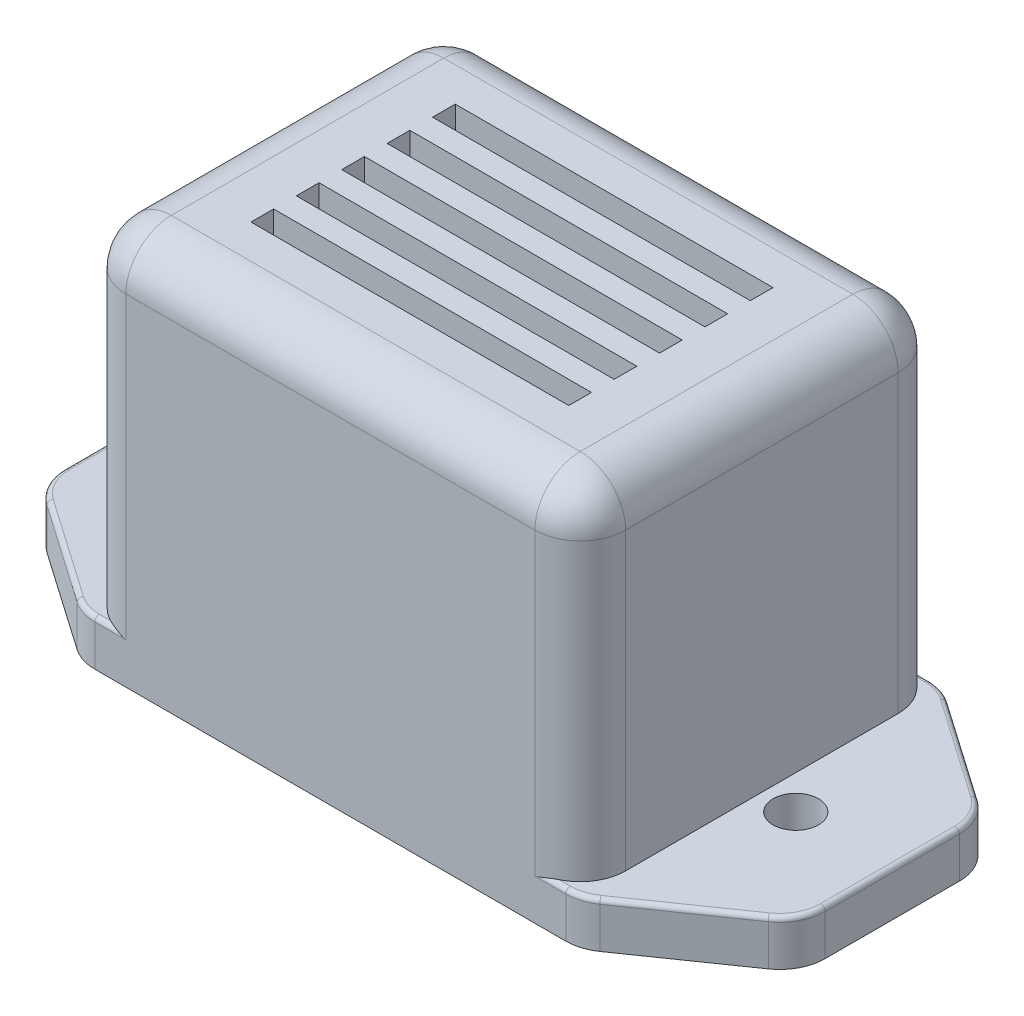
SolidWorks part; units mm, degrees
ref_plane "前视基准面" through (0, 0, 0) normal (0, 0, 1) x (1, 0, 0)
ref_plane "上视基准面" through (0, 0, 0) normal (0, 1, 0) x (1, 0, 0)
ref_plane "右视基准面" through (0, 0, 0) normal (1, 0, 0) x (0, 0, -1)
sketch "草图1" plane through (0, 0, 0) normal (0, 1, 0) x (1, 0, 0)
  line L0 (0, 0) -> (-16.75, 0) construction
  line L1 (-16.75, -4) -> (-16.75, 4)
  line L3 (10.3728, 8) -> (-10.3728, 8)
  line L4 (10.3728, -8) -> (-10.3728, -8)
  line L6 (11, 8) -> (-11, -8) construction
  line L7 (11, -8) -> (-11, 8) construction
  line L8 (0, 0) -> (0, 8) construction
  line L9 (-16.75, 4) -> (-11.5149, 7.6418)
  line L10 (-16.75, -4) -> (-11.5149, -7.6418)
  line L11 (16.75, -4) -> (11.5149, -7.6418)
  line L12 (16.75, -4) -> (16.75, 4)
  line L13 (16.75, 4) -> (11.5149, 7.6418)
  arc A0 (-10.3728, 8) -> (-11.5149, 7.6418) centre (-10.3728, 6) ccw
  arc A1 (10.3728, 8) -> (11.5149, 7.6418) centre (10.3728, 6) cw
  arc A2 (10.3728, -8) -> (11.5149, -7.6418) centre (10.3728, -6) ccw
  arc A3 (-10.3728, -8) -> (-11.5149, -7.6418) centre (-10.3728, -6) cw
  dimension "D5" = 4
  dimension "D1" = 16.75
  dimension "D2" = 4
  dimension "D3" = 22
  dimension "D4" = 16
extrude "凸台-拉伸1" add sketch "草图1" along normal blind 2
sketch "草图2" plane through (0, 2, 0) normal (0, 1, 0) x (1, 0, 0)
  line L0 (11.0073, 8) -> (11.0073, -8)
  line L1 (11.0073, 8) -> (-11.0073, 8)
  line L2 (11.0073, -8) -> (-11.0073, -8)
  line L3 (-11.0073, 8) -> (-11.0073, -8)
  line L4 (11.0073, 8) -> (-11.0073, -8) construction
  line L5 (11.0073, -8) -> (-11.0073, 8) construction
  point P1 (0, 0)
extrude "凸台-拉伸2" add sketch "草图2" along normal blind 15
sketch "草图3" plane through (0, 0, 0) normal (0, -1, 0) x (1, 0, 0)
  line L0 (0, 0) -> (-12.5, 0) construction
  circle A0 centre (-12.5, 0) radius 1
  dimension "D2" = 2
  dimension "D1" = 12.5
extrude "切除-拉伸1" cut sketch "草图3" against normal up to next
mirror "镜向1" about plane through (0, 0, 0) normal (1, 0, 0) of "切除-拉伸1"
sketch "草图4" plane through (0, 17, 0) normal (0, 1, 0) x (1, 0, 0)
  line L0 (0, 0) -> (-7, 0) construction
  line L1 (0, 0) -> (7, 0) construction
  line L2 (0, 0.5) -> (7, 0.5)
  line L3 (0, 0.5) -> (-7, 0.5)
  line L4 (0, -0.5) -> (7, -0.5)
  line L5 (0, -0.5) -> (-7, -0.5)
  line L6 (-7, 0.5) -> (-7, -0.5)
  line L7 (7, 0.5) -> (7, -0.5)
  dimension "D1" = 7
  dimension "D2" = 7
  dimension "D3" = 0.5
  dimension "D4" = 0.5
extrude "切除-拉伸2" cut sketch "草图4" against normal blind 1
pattern_linear "阵列(线性)1" count 3 spacing 2 along (0, 0, 1) count 3 spacing 2 along (0, 0, -1) of "切除-拉伸2"
sketch "草图5" plane through (0, 16, 0) normal (0, 1, 0) x (1, 0, 0)
  line L0 (9, 6) -> (9, -6)
  line L1 (9, 6) -> (-9, 6)
  line L2 (9, -6) -> (-9, -6)
  line L3 (-9, 6) -> (-9, -6)
  line L4 (9, 6) -> (-9, -6) construction
  line L5 (9, -6) -> (-9, 6) construction
  point P1 (0, 0)
  dimension "D1" = 18
  dimension "D2" = 12
extrude "切除-拉伸3" cut sketch "草图5" against normal blind 5
fillet "圆角4" radius 2 4 edges at (-16.75, 1, -4) (-16.75, 1, 4) (16.75, 1, -4) (16.75, 1, 4)
sketch "草图8" plane through (0, 17, 0) normal (0, 1, 0) x (1, 0, 0)
  line L4 (11.0073, 8) -> (-11.0073, 8)
  line L5 (-11.0073, 8) -> (-11.0073, -8)
  line L6 (-11.0073, -8) -> (11.0073, -8)
  line L7 (11.0073, -8) -> (11.0073, 8)
  line L8 (-9.0073, 8) -> (-11.0073, 8)
  line L9 (-11.0073, 8) -> (-11.0073, 6)
  arc A0 (-9.0073, 8) -> (-11.0073, 6) centre (-9.0073, 6) ccw
  dimension "D2" = 4
  dimension "D1" = 0
extrude "切除-拉伸5" cut sketch "草图8" against normal blind 15
mirror "镜向2" about plane through (0, 0, 0) normal (1, 0, 0) of "切除-拉伸5"
mirror "镜向3" about plane through (0, 0, 0) normal (0, 0, 1) of "切除-拉伸5", "镜向2"
fillet "圆角6" radius 0.2 22 edges at (13.7035, 2, 6.1193) (-16.75, 2, 0) (-13.7035, 2, 6.1193) (-16.5226, 2, 3.8812) (-16.5226, 2, -3.8812) (13.7035, 2, -6.1193) (16.75, 2, 0) (16.5226, 2, 3.8812) (16.5226, 2, -3.8812) (-13.7035, 2, -6.1193)
fillet "圆角7" radius 2 8 edges at (-10.4215, 17, -7.4142) (0, 17, -8) (10.4215, 17, -7.4142) (11.0073, 17, 0) (10.4215, 17, 7.4142) (0, 17, 8) (-10.4215, 17, 7.4142) (-11.0073, 17, 0)
